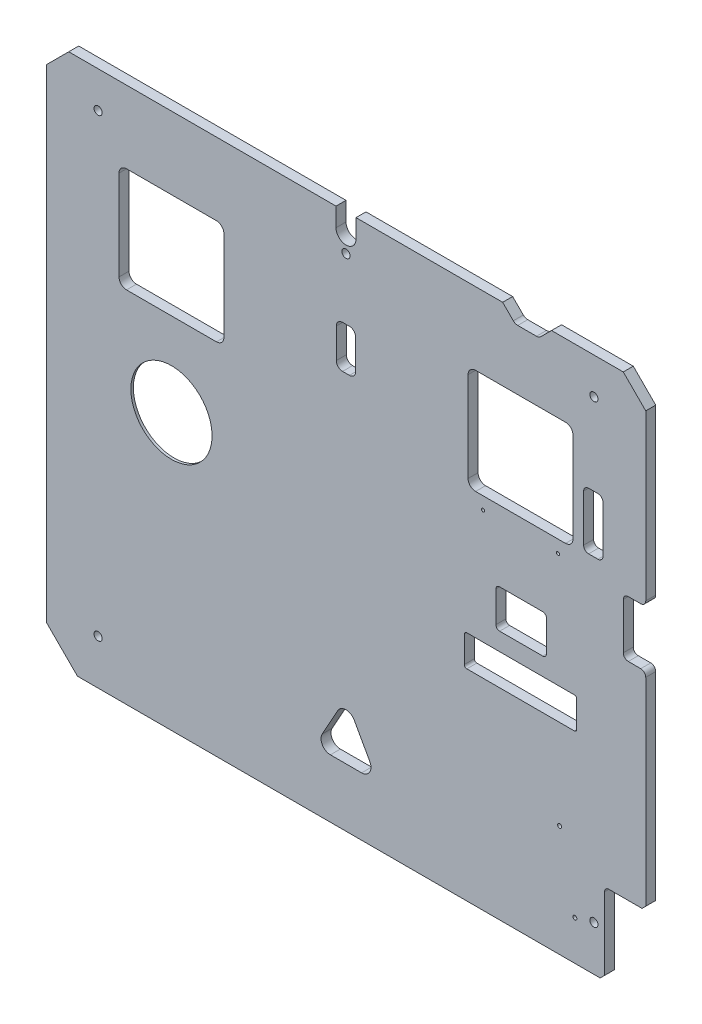
SolidWorks part; units mm, degrees
ref_plane "Front" through (0, 0, 0) normal (0, 0, 1) x (1, 0, 0)
ref_plane "Top" through (0, 0, 0) normal (0, 1, 0) x (1, 0, 0)
ref_plane "Right" through (0, 0, 0) normal (1, 0, 0) x (0, 0, -1)
ref_plane "Plane1" through (0, 0, 8) normal (0, 0, 1) x (1, 0, 0)
sketch "Sketch1" plane through (0, 0, 8) normal (0, 0, 1) x (1, 0, 0)
  line L0 (152.5, 201.25) -> (137.5, 201.25)
  line L1 (133.9645, 202.7145) -> (125.4289, 211.25)
  line L2 (125.4289, 211.25) -> (-222, 211.25)
  line L3 (-222, 211.25) -> (-240, 193.25)
  line L4 (-240, 193.25) -> (-240, -193.25)
  line L5 (-240, -193.25) -> (-215, -218.25)
  line L6 (-215, -218.25) -> (203.5, -218.25)
  line L7 (203.5, -218.25) -> (208.5, -213.25)
  line L8 (208.5, -213.25) -> (208.5, -157.25)
  line L9 (210.5, -155.25) -> (235, -155.25)
  line L10 (235, -155.25) -> (240, -150.25)
  line L11 (240, -150.25) -> (240, 8.5)
  line L12 (236, 12.5) -> (226, 12.5)
  line L13 (222, 16.5) -> (222, 53.5)
  line L14 (226, 57.5) -> (236, 57.5)
  line L15 (240, 61.5) -> (240, 193.25)
  line L16 (240, 193.25) -> (222, 211.25)
  line L17 (222, 211.25) -> (164.5711, 211.25)
  line L18 (164.5711, 211.25) -> (156.0355, 202.7145)
  line L19 (0, 201.25) -> (0, 0) construction
  line L20 (0, 0) -> (-180.6483, 0) construction
  line L21 (222, 35) -> (250.2434, 35) construction
  line L22 (145, 230.6041) -> (145, 201.25) construction
  arc A0 (156.0355, 202.7145) -> (152.5, 201.25) centre (152.5, 206.25) cw
  arc A1 (137.5, 201.25) -> (133.9645, 202.7145) centre (137.5, 206.25) cw
  arc A2 (208.5, -157.25) -> (210.5, -155.25) centre (210.5, -157.25) cw
  arc A3 (240, 8.5) -> (236, 12.5) centre (236, 8.5) ccw
  arc A4 (226, 12.5) -> (222, 16.5) centre (226, 16.5) cw
  arc A5 (222, 53.5) -> (226, 57.5) centre (226, 53.5) cw
  arc A6 (236, 57.5) -> (240, 61.5) centre (236, 61.5) ccw
  dimension "D13" = 2
  dimension "D17" = 4
  dimension "D20" = 5
  dimension "D1" = 480
  dimension "D2" = 211.25
  dimension "D3" = 218.25
  dimension "D4" = 45
  dimension "D5" = 18
  dimension "D6" = 45
  dimension "D7" = 25
  dimension "D8" = 31.5
  dimension "D9" = 63
  dimension "D10" = 45
  dimension "D11" = 5
  dimension "D12" = 5
  dimension "D14" = 35
  dimension "D15" = 45
  dimension "D16" = 18
  dimension "D18" = 145
  dimension "D19" = 10
  dimension "D21" = 15
extrude "Boss-Extrude1" add sketch "Sketch1" against normal blind 8
hole_wizard "Ø6.5 (6.5) Diameter Hole1" positions "Sketch3" profile "Sketch2" hole size "Ø6.5" standard "ANSI Metric"
sketch "Sketch3" plane through (0, 0, 8) normal (0, 0, 1) x (1, 0, 0)
  point P0 (198.5, -182.25)
  point P1 (0, 182.25)
  point P2 (-198.5, -182.25)
  point P3 (198.5, 182.25)
  point P4 (-198.5, 182.25)
sketch "Sketch2" plane through (198.5, -182.25, 8) normal (1, 0, 0) x (0, -1, 0)
  line L0 (0, 0) -> (0, 8)
  line L1 (0, 8) -> (3.25, 8)
  line L2 (3.25, 8) -> (3.25, 0)
  line L5 (3.25, 0) -> (0, 0)
  line L11 (0, -6.35) -> (0, 107.95) construction
  dimension "Thru Hole Dia." = 6.5
  dimension "Thru Hole Depth" = 8
sketch "Sketch4" plane through (0, 0, 0) normal (0, 0, -1) x (-1, 0, 0)
  line L0 (-6.5562, -137.8577) -> (-19.0562, -160.3577)
  line L1 (-12.5, -171.5) -> (12.5, -171.5)
  line L2 (19.0562, -160.3577) -> (6.5562, -137.8577)
  line L3 (0, 0) -> (0, -171.5) construction
  line L4 (0, -141.5) -> (-12.5, -164) construction
  line L5 (-12.5, -164) -> (12.5, -164) construction
  line L6 (12.5, -164) -> (0, -141.5) construction
  arc A0 (6.5562, -137.8577) -> (-6.5562, -137.8577) centre (0, -141.5) ccw
  arc A1 (-19.0562, -160.3577) -> (-12.5, -171.5) centre (-12.5, -164) ccw
  arc A2 (12.5, -171.5) -> (19.0562, -160.3577) centre (12.5, -164) ccw
  dimension "D1" = 7.5
  dimension "D2" = 25
  dimension "D3" = 22.5
  dimension "D4" = 171.5
extrude "Cut-Extrude1" cut sketch "Sketch4" against normal through all
sketch "Sketch12" plane through (0, 0, 0) normal (0, 0, -1) x (-1, 0, 0)
  line L1 (103.75, 153.25) -> (175.75, 153.25)
  line L2 (97.75, 147.25) -> (97.75, 75.25)
  line L3 (103.75, 69.25) -> (175.75, 69.25)
  line L4 (181.75, 147.25) -> (181.75, 75.25)
  line L5 (-125.4289, 211.25) -> (222, 211.25) construction
  line L6 (0, 211.25) -> (0, 0) construction
  line L7 (0, 0) -> (186.7318, 0) construction
  line L8 (240, 193.25) -> (240, -193.25) construction
  line L9 (123, 12.75) -> (157.5, 12.75)
  line L10 (120, 9.75) -> (120, -15)
  line L11 (123, -18) -> (157.5, -18)
  line L12 (160.5, 9.75) -> (160.5, -15)
  arc A0 (97.75, 75.25) -> (103.75, 69.25) centre (103.75, 75.25) ccw
  arc A1 (103.75, 153.25) -> (97.75, 147.25) centre (103.75, 147.25) ccw
  arc A2 (175.75, 153.25) -> (181.75, 147.25) centre (175.75, 147.25) cw
  arc A3 (175.75, 69.25) -> (181.75, 75.25) centre (175.75, 75.25) ccw
  arc A4 (120, -15) -> (123, -18) centre (123, -15) ccw
  arc A5 (120, 9.75) -> (123, 12.75) centre (123, 9.75) cw
  arc A6 (157.5, 12.75) -> (160.5, 9.75) centre (157.5, 9.75) cw
  arc A7 (157.5, -18) -> (160.5, -15) centre (157.5, -15) ccw
  dimension "D4" = 6
  dimension "D10" = 3
  dimension "D1" = 84
  dimension "D2" = 84
  dimension "D3" = 195.5
  dimension "D5" = 69.25
  dimension "D6" = 79.5
  dimension "D7" = 40.5
  dimension "D8" = 56.5
  dimension "D9" = 30.75
extrude "Cut-Extrude6" cut sketch "Sketch12" against normal up to next
mirror "Mirror1" about plane through (0, 0, 0) normal (1, 0, 0) of "Cut-Extrude6"
sketch "Sketch11" plane through (0, 0, 0) normal (0, 0, -1) x (-1, 0, 0)
  line L0 (0, 0) -> (0, 211.25) construction
  line L1 (-2.75, 133.25) -> (2.75, 133.25)
  line L2 (-7.75, 128.25) -> (-7.75, 104.25)
  line L3 (-2.75, 99.25) -> (2.75, 99.25)
  line L4 (7.75, 128.25) -> (7.75, 104.25)
  line L5 (-125.4289, 211.25) -> (222, 211.25) construction
  line L6 (-222, 211.25) -> (-164.5711, 211.25) construction
  line L7 (-201.75, 116.75) -> (-194.25, 116.75)
  line L8 (-205.75, 112.75) -> (-205.75, 75.25)
  line L9 (-201.75, 71.25) -> (-194.25, 71.25)
  line L10 (-190.25, 112.75) -> (-190.25, 75.25)
  line L12 (-181.75, 75.25) -> (-181.75, 147.25) construction
  arc A0 (2.75, 99.25) -> (7.75, 104.25) centre (2.75, 104.25) ccw
  arc A1 (-7.75, 104.25) -> (-2.75, 99.25) centre (-2.75, 104.25) ccw
  arc A2 (-2.75, 133.25) -> (-7.75, 128.25) centre (-2.75, 128.25) ccw
  arc A3 (2.75, 133.25) -> (7.75, 128.25) centre (2.75, 128.25) cw
  arc A4 (-205.75, 75.25) -> (-201.75, 71.25) centre (-201.75, 75.25) ccw
  arc A5 (-194.25, 71.25) -> (-190.25, 75.25) centre (-194.25, 75.25) ccw
  arc A6 (-194.25, 116.75) -> (-190.25, 112.75) centre (-194.25, 112.75) cw
  arc A7 (-201.75, 116.75) -> (-205.75, 112.75) centre (-201.75, 112.75) ccw
  point P11 (7.75, 99.25)
  point P18 (7.75, 133.25)
  dimension "D4" = 5
  dimension "D9" = 4
  dimension "D1" = 34
  dimension "D2" = 15.5
  dimension "D3" = 78
  dimension "D5" = 15.5
  dimension "D6" = 45.5
  dimension "D7" = 94.5
  dimension "D8" = 8.5
extrude "Cut-Extrude7" cut sketch "Sketch11" against normal up to next
sketch "Sketch9" plane through (0, 0, 0) normal (0, 0, -1) x (-1, 0, 0)
  line L0 (0, 51.3888) -> (0, 0) construction
  line L1 (0, 0) -> (200.3216, 0) construction
  line L2 (139.75, 69.25) -> (139.75, 34.75) construction
  line L4 (103.75, 69.25) -> (175.75, 69.25) construction
  circle A1 centre (139.75, 2.25) radius 32.5
  dimension "D2" = 65
  dimension "D1" = 34.5
extrude "Cut-Extrude5" cut sketch "Sketch9" against normal up to next
chamfer "Chamfer1" distance 9 distance2 6 1 edges at (-172.25, 2.25, 0)
sketch "Sketch13" plane through (0, 0, 8) normal (0, 0, 1) x (1, 0, 0)
  line L0 (191.8313, 0) -> (0, 0) construction
  line L1 (0, 0) -> (0, -200.2802) construction
  circle A1 centre (171, -129) radius 1.6
  circle A3 centre (183.25, -186.6) radius 1.6
  dimension "D5" = 3.2
  dimension "D1" = 129
  dimension "D2" = 171
  dimension "D3" = 57.6
  dimension "D4" = 12.25
extrude "Cut-Extrude8" cut sketch "Sketch13" against normal up to next
sketch "Sketch14" plane through (0, 0, 8) normal (0, 0, 1) x (1, 0, 0)
  line L0 (0, 245.6851) -> (0, 196.25) construction
  line L1 (8, 245.6851) -> (8, 196.25)
  line L2 (-8, 245.6851) -> (-8, 196.25)
  line L3 (125.4289, 211.25) -> (-222, 211.25) construction
  arc A0 (8, 245.6851) -> (-8, 245.6851) centre (0, 245.6851) ccw
  arc A1 (-8, 196.25) -> (8, 196.25) centre (0, 196.25) ccw
  point P3 (0, 220.9675)
  dimension "D1" = 16
  dimension "D2" = 15
extrude "Cut-Extrude9" cut sketch "Sketch14" against normal up to next
sketch "Sketch15" plane through (0, 0, 0) normal (0, 0, -1) x (-1, 0, 0)
  line L4 (-240, -153.25) -> (-240, -218.25)
  line L5 (-240, -218.25) -> (-207, -218.25)
  line L6 (-208.5, -213.25) -> (-208.5, -157.25) construction
  line L7 (-210.5, -155.25) -> (-235, -155.25) construction
  line L8 (-207, -218.25) -> (-207, -156.75)
  line L9 (-210.5, -153.25) -> (-240, -153.25)
  line L10 (215, -218.25) -> (-203.5, -218.25) construction
  line L11 (-240, -150.25) -> (-240, 8.5) construction
  arc A4 (-207, -156.75) -> (-210.5, -153.25) centre (-210.5, -156.75) ccw
  dimension "D3" = 3.5
  dimension "D1" = 1.5
  dimension "D2" = 2
extrude "Cut-Extrude10" cut sketch "Sketch15" against normal through all
sketch "Sketch16" plane through (0, 0, 0) normal (0, 0, -1) x (-1, 0, 0)
  line L0 (-169.75, 59.25) -> (-109.75, 59.25) construction
  line L1 (-139.75, 69.25) -> (-139.75, 12.7481) construction
  line L2 (-103.75, 69.25) -> (-175.75, 69.25) construction
  line L6 (-182.75, -32.25) -> (-96.75, -32.25)
  line L7 (-184.75, -34.25) -> (-184.75, -55.25)
  line L8 (-182.75, -57.25) -> (-96.75, -57.25)
  line L9 (-94.75, -34.25) -> (-94.75, -55.25)
  line L10 (-183.75, -27.75) -> (-95.75, -27.75) construction
  line L11 (-189.75, -33.75) -> (-189.75, -56.75) construction
  line L12 (-183.75, -62.75) -> (-95.75, -62.75) construction
  line L13 (-89.75, -33.75) -> (-89.75, -56.75) construction
  circle A0 centre (-169.75, 59.25) radius 1.25
  circle A1 centre (-109.75, 59.25) radius 1.25
  arc A2 (-189.75, -56.75) -> (-183.75, -62.75) centre (-183.75, -56.75) ccw construction
  arc A3 (-95.75, -62.75) -> (-89.75, -56.75) centre (-95.75, -56.75) ccw construction
  arc A4 (-89.75, -33.75) -> (-95.75, -27.75) centre (-95.75, -33.75) ccw construction
  arc A5 (-189.75, -33.75) -> (-183.75, -27.75) centre (-183.75, -33.75) cw construction
  arc A6 (-184.75, -55.25) -> (-182.75, -57.25) centre (-182.75, -55.25) ccw
  arc A7 (-182.75, -32.25) -> (-184.75, -34.25) centre (-182.75, -34.25) ccw
  arc A8 (-96.75, -57.25) -> (-94.75, -55.25) centre (-96.75, -55.25) ccw
  arc A9 (-96.75, -32.25) -> (-94.75, -34.25) centre (-96.75, -34.25) cw
  point P22 (-89.75, -27.75)
  point P25 (-189.75, -27.75)
  dimension "D1" = 2.5
  dimension "D8" = 6
  dimension "D11" = 2
  dimension "D2" = 25
  dimension "D3" = 90
  dimension "D4" = 116.5
  dimension "D5" = 97
  dimension "D6" = 35
  dimension "D7" = 100
  dimension "D9" = 10
  dimension "D10" = 60
extrude "Cut-Extrude11" cut sketch "Sketch16" against normal up to next
